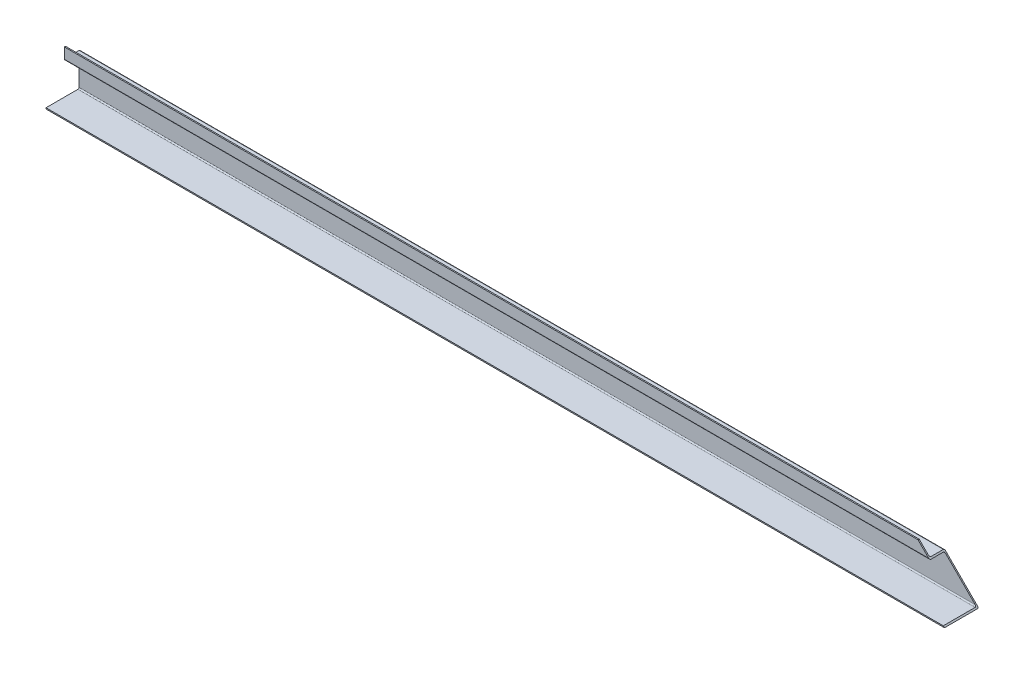
SolidWorks part; units mm, degrees
ref_plane "Front Plane" through (0, 0, 0) normal (0, 0, 1) x (1, 0, 0)
ref_plane "Top Plane" through (0, 0, 0) normal (0, 1, 0) x (1, 0, 0)
ref_plane "Right Plane" through (0, 0, 0) normal (1, 0, 0) x (0, 0, -1)
sketch "Sketch1" plane through (0, 0, 0) normal (1, 0, 0) x (0, 0, -1)
  line L0 (0, 0) -> (85, 0)
  line L1 (85, 0) -> (85, 82)
  line L2 (85, 82) -> (47, 82)
  line L3 (47, 82) -> (47, 112)
  line L4 (0, -3) -> (88, -3)
  line L5 (88, -3) -> (88, 85)
  line L6 (88, 85) -> (50, 85)
  line L7 (50, 85) -> (50, 112)
  line L8 (47, 112) -> (50, 112)
  line L9 (0, 0) -> (0, -3)
  point P11 (48.5, 112)
  dimension "D1" = 3
  dimension "D2" = 27
  dimension "D3" = 38
  dimension "D4" = 88
  dimension "D5" = 88
extrude "Boss-Extrude1" add sketch "Sketch1" along normal blind 2310
fillet "Fillet1" radius 3 6 edges at (1155, -3, -88) (1155, 85, -88) (1155, 85, -50) (1155, 82, -85) (1155, 0, -85) (1155, 82, -47)
sketch "Sketch4" plane through (0, 0, -88) normal (0, 0, -1) x (-1, 0, 0)
  line L0 (-2310, -3) -> (-2195, 112)
  line L1 (-2310, 112) -> (0, 112) construction
  line L2 (-2195, 112) -> (-2310, 112)
  line L3 (-2310, 112) -> (-2310, -3)
  dimension "D1" = 45
extrude "Cut-Extrude1" cut sketch "Sketch4" against normal blind 88
equation "\"D1@Boss-Extrude1\"= \"indoorHeight\" + \"indoorHeight_para\" + 80 + \"rearLightHeight_para\""
equation "\"CarBeamWidth\"=700.0"
equation "\"WheelWidth\"=650.0"
equation "\"Wheel_FrontBoxDistance\"=1390.0"
equation "\"boxLength\"=5100.0"
equation "\"boxWidth\"=1930.0"
equation "\"MetalSheet_3mm_length\"=5030.0"
equation "\"MetalSheet_3mm_width\"=1923.0"
equation "\"MetalSheet_3mm_FloorCut_L_length\"=1764.0"
equation "\"MetalSheet_3mm_FloorCut_L_disdance\"=1665.0"
equation "\"MetalSheet_3mm_FloorCut_R_length\"=1764.0"
equation "\"MetalSheet_3mm_FloorCut_R_disdance\"=1665.0"
equation "\"indoorHeight\"=1940.0"
equation "\"indoorHeight_para\"=25.0"
equation "\"rearLightHeight_para\"=265.0"
equation "\"haveDoor_R\"=1"
equation "\"side_door_bottom_R_3mm_length\"=1934.0"
equation "\"side_door_bottom_R_3mm_toFrontDistance\"=1583.0"
equation "\"1Bar_Side_RF_3mm_length\"=1493.0"
equation "\"1Bar_Side_RB_3mm_length\"=1493.0"
equation "\"DoorSeparator_RF_3mm_withHinge_toFrontDistance\"=1673.0"
equation "\"DoorSeparator_RF_3mm_withHinge_exist\"=1"
equation "\"DoorSeparator_RB_3mm_withHinge_toFrontDistance\"=3427.0"
equation "\"DoorSeparator_RB_3mm_withHinge_exist\"=1"
equation "\"Door_R1_L_open_Single_toFrontDistance\"=2547.5"
equation "\"Door_R1_L_open_Single_exist\"=1"
equation "\"door_base_long7_R1_L_open_Single_height\"=1890.0"
equation "\"door_base_short7_R1_L_open_Single_height\"=1890.0"
equation "\"door_base_short7_R1_L_open_Single_width\"=864"
equation "\"Door_R1_R_open_Single_toFrontDistance\"=3422.0"
equation "\"Door_R1_R_open_Single_exist\"=1"
equation "\"door_base_long7_R1_R_open_Single_height\"=1890.0"
equation "\"door_base_short7_R1_R_open_Single_height\"=1890.0"
equation "\"door_base_short7_R1_R_open_Single_width\"=864"
equation "\"x\"=66.0"
equation "\"da\"=62.0"
equation "\"SquareTube_length\"=1923.0"
equation "\"channelSteel_length\"=5030.0"
equation "\"SquareTube_inFront_AvgDistance\"=285.0"
equation "\"SquareTube_inFront_TotalCount\"=5"
equation "\"SquareTube_inFront1_cutDepth50_R\"=0.5"
equation "\"SquareTube_inFront1_cutDepth50_L\"=0.5"
equation "\"SquareTube_inFront2_cutDepth50_R\"=0.5"
equation "\"SquareTube_inFront2_cutDepth50_L\"=0.5"
equation "\"SquareTube_inFront3_cutDepth50_R\"=0.5"
equation "\"SquareTube_inFront3_cutDepth50_L\"=0.5"
equation "\"SquareTube_inFront4_cutDepth50_R\"=0.5"
equation "\"SquareTube_inFront4_cutDepth50_L\"=0.5"
equation "\"SquareTube_inFront5_cutDepth50_R\"=50"
equation "\"SquareTube_inFront5_cutDepth50_L\"=50"
equation "\"SquareTube_inFront6_cutDepth50_R\"=50"
equation "\"SquareTube_inFront6_cutDepth50_L\"=50"
equation "\"SquareTube_inFront7_cutDepth50_R\"=50"
equation "\"SquareTube_inFront7_cutDepth50_L\"=50"
equation "\"SquareTube_inFront8_cutDepth50_R\"=50"
equation "\"SquareTube_inFront8_cutDepth50_L\"=50"
equation "\"SquareTube_inFront9_cutDepth50_R\"=50"
equation "\"SquareTube_inFront9_cutDepth50_L\"=50"
equation "\"SquareTube_inFront10_cutDepth50_R\"=50"
equation "\"SquareTube_inFront10_cutDepth50_L\"=50"
equation "\"SquareTube_inFront11_cutDepth50_R\"=50"
equation "\"SquareTube_inFront11_cutDepth50_L\"=50"
equation "\"SquareTube_inFront12_cutDepth50_R\"=50"
equation "\"SquareTube_inFront12_cutDepth50_L\"=50"
equation "\"SquareTube_inFront13_cutDepth50_R\"=50"
equation "\"SquareTube_inFront13_cutDepth50_L\"=50"
equation "\"SquareTube_inFront14_cutDepth50_R\"=50"
equation "\"SquareTube_inFront14_cutDepth50_L\"=50"
equation "\"SquareTube_inBack_AvgDistance\"=333.125"
equation "\"SquareTube_inBack_TotalCount\"=9"
equation "\"SquareTube_inBack1_cutDepth50_R\"=50"
equation "\"SquareTube_inBack1_cutDepth50_L\"=50"
equation "\"SquareTube_inBack2_cutDepth50_R\"=50"
equation "\"SquareTube_inBack2_cutDepth50_L\"=50"
equation "\"SquareTube_inBack3_cutDepth50_R\"=50"
equation "\"SquareTube_inBack3_cutDepth50_L\"=50"
equation "\"SquareTube_inBack4_cutDepth50_R\"=50"
equation "\"SquareTube_inBack4_cutDepth50_L\"=50"
equation "\"SquareTube_inBack5_cutDepth50_R\"=50"
equation "\"SquareTube_inBack5_cutDepth50_L\"=50"
equation "\"SquareTube_inBack6_cutDepth50_R\"=0.5"
equation "\"SquareTube_inBack6_cutDepth50_L\"=0.5"
equation "\"SquareTube_inBack7_cutDepth50_R\"=0.5"
equation "\"SquareTube_inBack7_cutDepth50_L\"=0.5"
equation "\"SquareTube_inBack8_cutDepth50_R\"=0.5"
equation "\"SquareTube_inBack8_cutDepth50_L\"=0.5"
